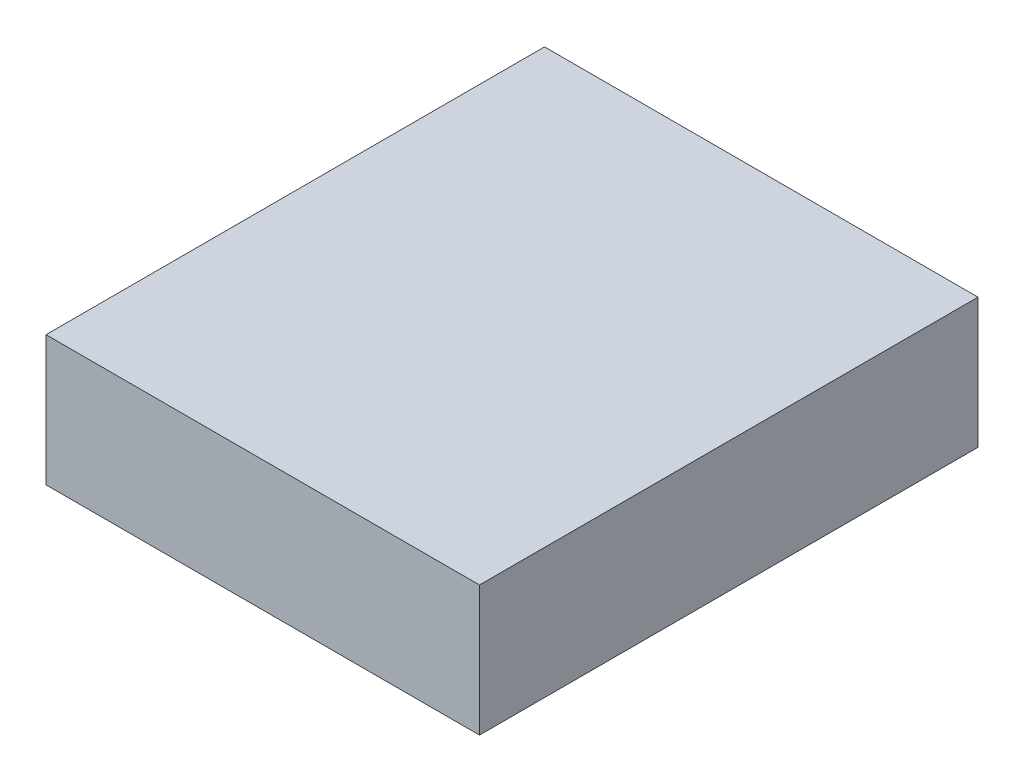
SolidWorks part; units mm, degrees
material "6061-T6 (SS)"
ref_plane "Front Plane" through (0, 0, 0) normal (0, 0, 1) x (1, 0, 0)
ref_plane "Top Plane" through (0, 0, 0) normal (0, 1, 0) x (1, 0, 0)
ref_plane "Right Plane" through (0, 0, 0) normal (1, 0, 0) x (0, 0, -1)
sketch "Sketch1" plane through (0, 0, 0) normal (0, 1, 0) x (1, 0, 0)
  line L1 (63.5, -73.025) -> (-63.5, -73.025)
  line L2 (63.5, -73.025) -> (63.5, 73.025)
  line L3 (63.5, 73.025) -> (-63.5, 73.025)
  line L4 (-63.5, -73.025) -> (-63.5, 73.025)
  line L5 (63.5, -73.025) -> (-63.5, 73.025) construction
  line L6 (63.5, 73.025) -> (-63.5, -73.025) construction
  point P0 (0, 0)
  dimension "D1" = 127
  dimension "D2" = 146.05
extrude "Boss-Extrude1" add sketch "Sketch1" along normal blind 38.1
